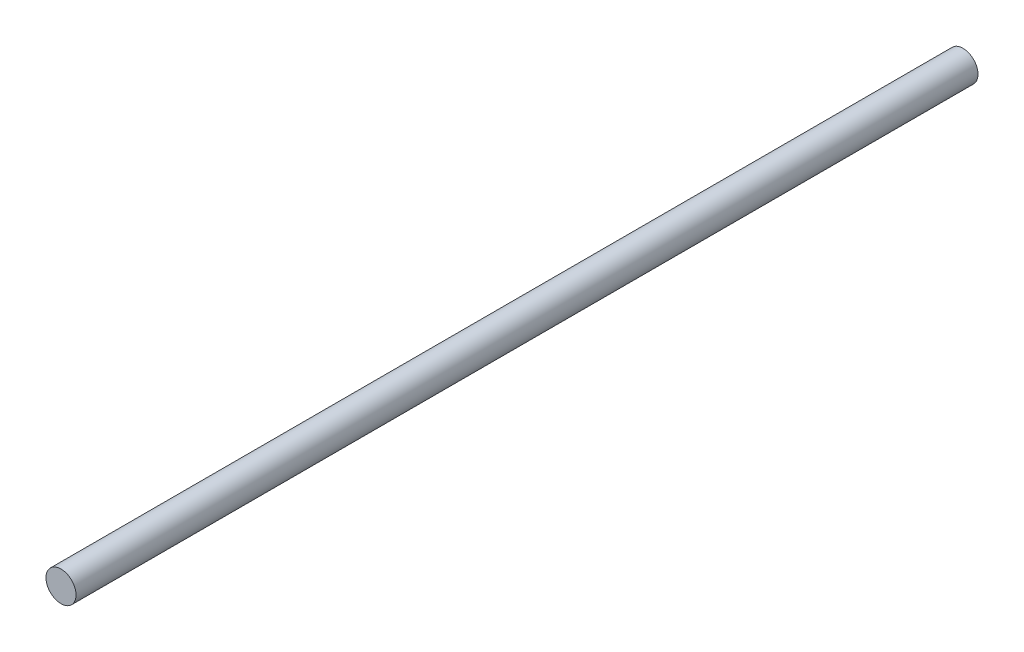
SolidWorks part; units mm, degrees
material "1023 Carbon Steel Sheet (SS)"
ref_plane "Front Plane" through (0, 0, 0) normal (0, 0, 1) x (1, 0, 0)
ref_plane "Top Plane" through (0, 0, 0) normal (0, 1, 0) x (1, 0, 0)
ref_plane "Right Plane" through (0, 0, 0) normal (1, 0, 0) x (0, 0, -1)
sketch "Sketch1" plane through (0, 0, 0) normal (0, 0, 1) x (1, 0, 0)
  circle A0 centre (0, 0) radius 1.5875
  dimension "D1" = 3.175
extrude "Boss-Extrude1" add sketch "Sketch1" along normal blind 95.25
